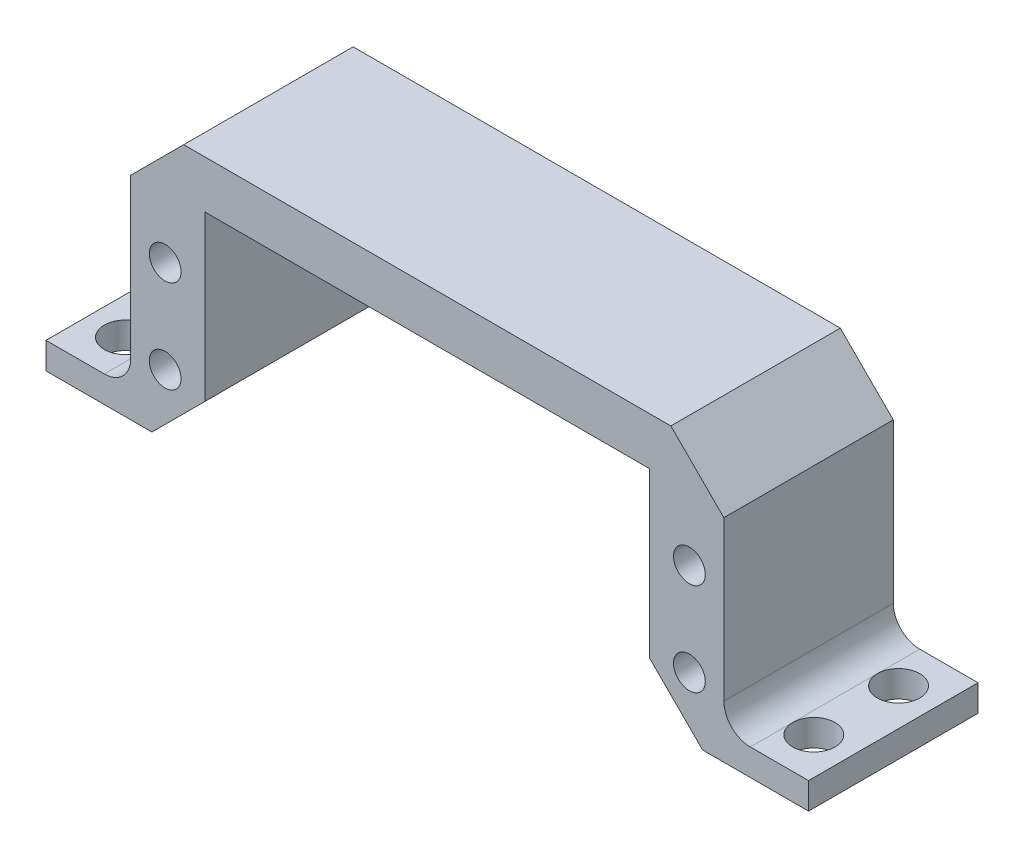
SolidWorks part; units mm, degrees
ref_plane "Front Plane" through (0, 0, 0) normal (0, 0, 1) x (1, 0, 0)
ref_plane "Top Plane" through (0, 0, 0) normal (0, 1, 0) x (1, 0, 0)
ref_plane "Right Plane" through (0, 0, 0) normal (1, 0, 0) x (0, 0, -1)
sketch "Sketch1" plane through (0, 0, 0) normal (0, 0, 1) x (1, 0, 0)
  line L0 (-36, 0) -> (-21, 0)
  line L1 (-21, 0) -> (-21, 20.5)
  line L2 (-21, 20.5) -> (21, 20.5)
  line L3 (21, 20.5) -> (21, 0)
  line L4 (21, 0) -> (36, 0)
  line L5 (-36, 0) -> (-36, 2.5)
  line L6 (-36, 2.5) -> (-28, 2.5)
  line L7 (36, 0) -> (36, 2.5)
  line L8 (36, 2.5) -> (28, 2.5)
  line L9 (-28, 2.5) -> (-28, 25)
  line L10 (-28, 25) -> (28, 25)
  line L11 (28, 25) -> (28, 2.5)
  dimension "D1" = 72
  dimension "D2" = 36
  dimension "D3" = 42
  dimension "D4" = 21
  dimension "D5" = 20.5
  dimension "D6" = 2.5
  dimension "D7" = 25
  dimension "D8" = 56
extrude "Boss-Extrude1" add sketch "Sketch1" along normal mid plane 16
chamfer "Chamfer5" distance 5 angle 45 4 edges at (-28, 25, 0) (21, 0, 0) (-21, 0, 0) (28, 25, 0)
fillet "Fillet1" radius 2.5 2 edges at (28, 2.5, 0) (-28, 2.5, 0)
sketch "Sketch2" plane through (0, 0, 8) normal (0, 0, 1) x (1, 0, 0)
  circle A0 centre (-24.75, 14.475) radius 1.5
  circle A1 centre (-24.75, 5.725) radius 1.5
  circle A2 centre (24.75, 14.475) radius 1.5
  circle A3 centre (24.75, 5.725) radius 1.5
  dimension "D1" = 3
  dimension "D5" = 14.475
  dimension "D3" = 49.5
  dimension "D4" = 24.75
  dimension "D6" = 8.75
extrude "Cut-Extrude1" cut sketch "Sketch2" against normal through all
sketch "Sketch3" plane through (0, 2.5, 0) normal (0, 1, 0) x (1, 0, 0)
  line L0 (36, -8) -> (36, 8) construction
  line L1 (30.5, 28.8859) -> (30.5, -25.0715) construction
  line L2 (-30.5, 27.8941) -> (-30.5, -24.0796) construction
  line L3 (-30.5, -8) -> (-30.5, 8) construction
  line L4 (30.5, 8) -> (30.5, -8) construction
  line L5 (56.6832, -8) -> (-41.1826, -8) construction
  line L6 (65.7079, 8) -> (-46.658, 8) construction
  line L7 (36, 8) -> (30.5, 8) construction
  line L8 (36, -8) -> (30.5, -8) construction
  line L9 (36, 29.9064) -> (36, -19.7738) construction
  circle A0 centre (32.5, 4) radius 2
  circle A1 centre (32.5, -4) radius 2
  circle A2 centre (-32.5, 4) radius 2
  circle A3 centre (-32.5, -4) radius 2
  dimension "D2" = 4
  dimension "D3" = 4
  dimension "D1" = 2
  dimension "D4" = 16
  dimension "D5" = 4
  dimension "D6" = 4
  dimension "D7" = 5.5
  dimension "D8" = 2
extrude "Cut-Extrude2" cut sketch "Sketch3" against normal through all
